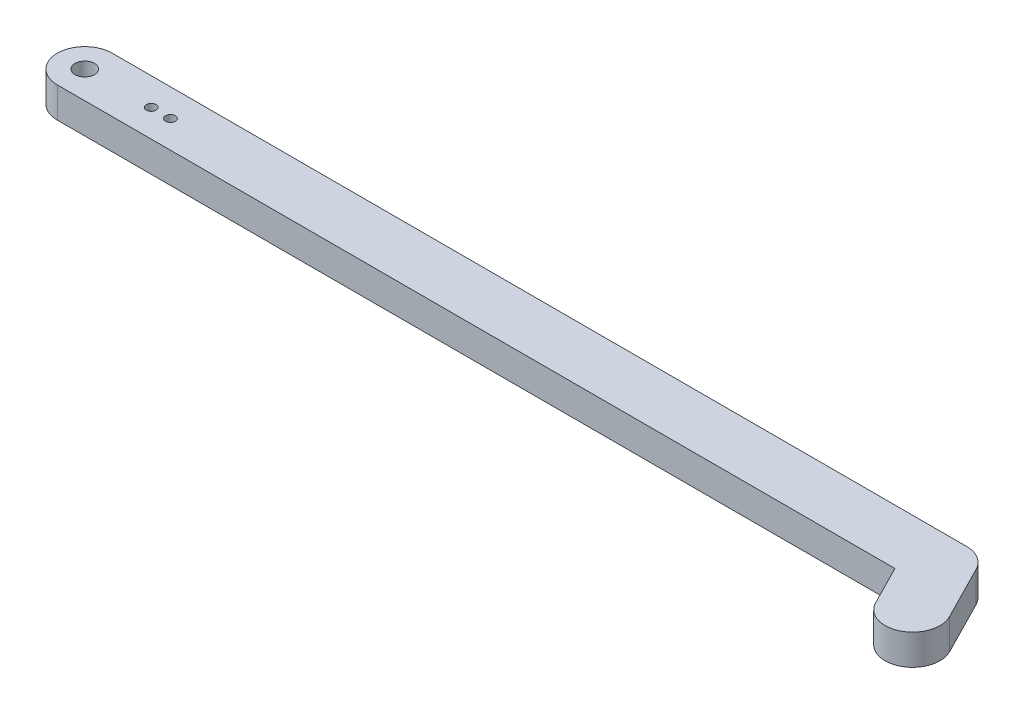
SolidWorks part; units mm, degrees
ref_plane "Front Plane" through (0, 0, 0) normal (0, 0, 1) x (1, 0, 0)
ref_plane "Top Plane" through (0, 0, 0) normal (0, 1, 0) x (1, 0, 0)
ref_plane "Right Plane" through (0, 0, 0) normal (1, 0, 0) x (0, 0, -1)
sketch "Sketch1" plane through (0, 0, 0) normal (0, 1, 0) x (1, 0, 0)
  line L0 (0, 0) -> (140, 0) construction
  line L2 (0, 4.5) -> (140, 4.5)
  line L3 (0, -4.5) -> (140, -4.5)
  line L4 (140, 0) -> (144.54, -8.91) construction
  line L5 (144.0095, 2.043) -> (148.5495, -6.867)
  line L6 (135.9905, -2.043) -> (140.5305, -10.953)
  arc A0 (0, 4.5) -> (0, -4.5) centre (0, 0) ccw
  arc A1 (140, -4.5) -> (140, 4.5) centre (140, 0) ccw
  arc A2 (144.0095, 2.043) -> (135.9905, -2.043) centre (140, 0) ccw
  arc A3 (140.5305, -10.953) -> (148.5495, -6.867) centre (144.54, -8.91) ccw
  circle A4 centre (0, 0) radius 1.6
  circle A5 centre (10.88, 0) radius 0.8
  circle A6 centre (14.03, 0) radius 0.8
  point P5 (70, 0)
  point P10 (142.27, -4.455)
  dimension "D1" = 140
  dimension "D2" = 4.5
  dimension "D3" = 4.5
  dimension "D4" = 10.88
  dimension "D5" = 1.6
  dimension "D6" = 3.15
extrude "Boss-Extrude1" add sketch "Sketch1" along normal blind 5 contours A2 L2 A0 L3 L6 A4 | A1 A2 L6 L3 | L6 A3 L5 A1 L3
